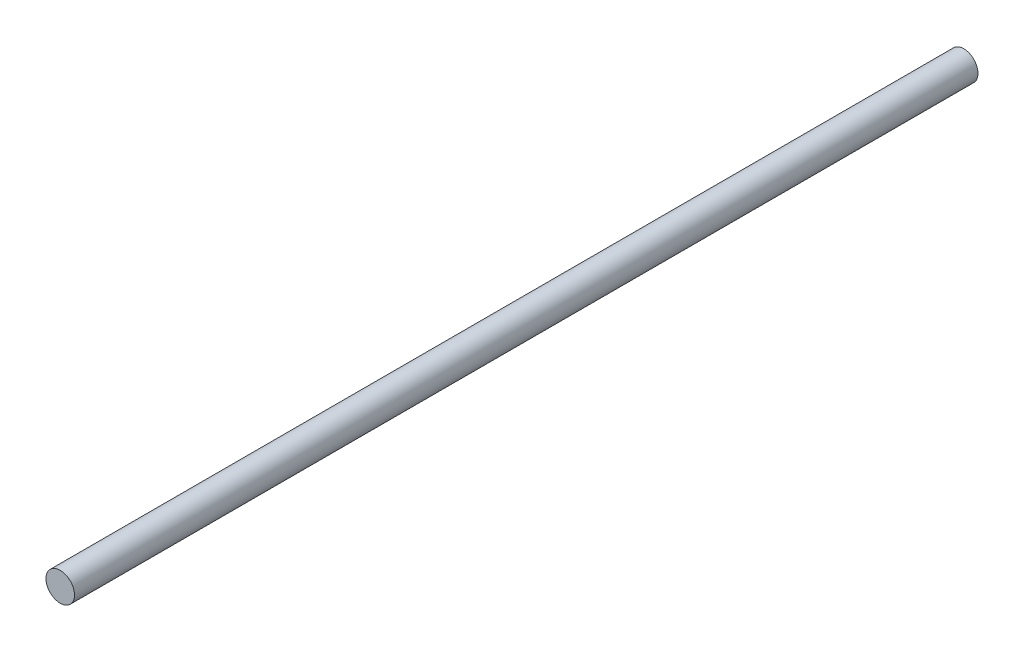
SolidWorks part; units mm, degrees
ref_plane "Front Plane" through (0, 0, 0) normal (0, 0, 1) x (1, 0, 0)
ref_plane "Top Plane" through (0, 0, 0) normal (0, 1, 0) x (1, 0, 0)
ref_plane "Right Plane" through (0, 0, 0) normal (1, 0, 0) x (0, 0, -1)
sketch "Sketch1" plane through (0, 0, 0) normal (0, 0, 1) x (1, 0, 0)
  circle A0 centre (0, 0) radius 3
  dimension "D1" = 6
extrude "Boss-Extrude1" add sketch "Sketch1" along normal blind 190
